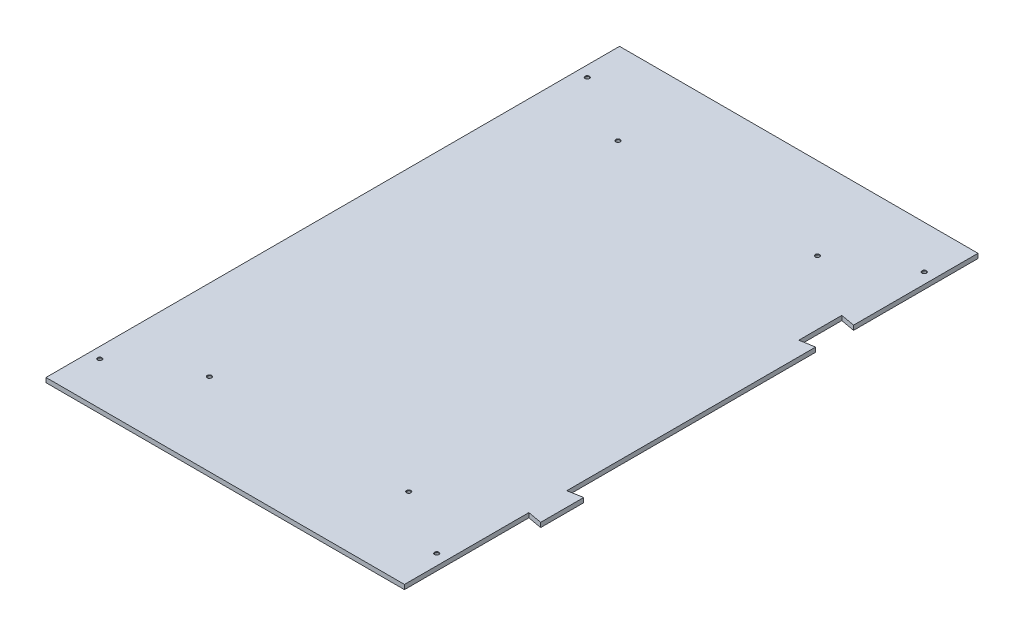
SolidWorks part; units mm, degrees
ref_plane "Front Plane" through (0, 0, 0) normal (0, 0, 1) x (1, 0, 0)
ref_plane "Top Plane" through (0, 0, 0) normal (0, 1, 0) x (1, 0, 0)
ref_plane "Right Plane" through (0, 0, 0) normal (1, 0, 0) x (0, 0, -1)
sketch "Sketch1" plane through (0, 0, 0) normal (0, 1, 0) x (1, 0, 0)
  line L0 (0, 0) -> (-99.9329, 0) construction
  line L1 (0, -19.2585) -> (0, 19.2585) construction
  line L2 (0, 86.7633) -> (-10, 85)
  line L3 (-10, 85) -> (-10, 115)
  line L4 (-10, 115) -> (0, 113.2367)
  line L5 (0, 113.2367) -> (0, 200)
  line L6 (0, 200) -> (-250, 200)
  line L7 (-250, 200) -> (-250, -200)
  line L8 (-10, 100) -> (-3.183, 100) construction
  line L9 (0, -86.7633) -> (0, 86.7633)
  line L10 (-10, -100) -> (-3.183, -100) construction
  line L11 (0, -200) -> (-250, -200)
  line L12 (0, -113.2367) -> (0, -200)
  line L16 (0, -86.7633) -> (0, -113.2367) construction
  line L17 (0, -86.7633) -> (10, -85)
  line L18 (10, -100) -> (3.183, -100) construction
  line L19 (10, -85) -> (10, -115)
  line L20 (10, -115) -> (0, -113.2367)
  point P19 (-250, 0)
  dimension "D1" = 20
  dimension "D2" = 80
  dimension "D3" = 80
  dimension "D4" = 30
  dimension "D5" = 100
  dimension "D6" = 200
  dimension "D7" = 80
  dimension "D8" = 80
  dimension "D9" = 30
  dimension "D10" = 250
extrude "Boss-Extrude1" add sketch "Sketch1" along normal blind 3.175
sketch "Sketch2" plane through (0, 3.175, 0) normal (0, 1, 0) x (1, 0, 0)
  line L0 (-250, -142.5) -> (-25.2029, -142.5) construction
  line L1 (-250, 200) -> (-250, -200) construction
  line L2 (-250, -200) -> (0, -200) construction
  line L3 (-250, 0) -> (-187.6563, 0) construction
  line L4 (-250, 142.5) -> (-25.2029, 142.5) construction
  line L5 (-242.5, -200) -> (-242.5, 200) construction
  line L6 (0, 200) -> (-250, 200) construction
  line L7 (-242.5, -170) -> (0, -170) construction
  line L8 (0, -200) -> (0, -113.2367) construction
  line L9 (-7.5, -200) -> (-7.5, -128.5966) construction
  line L10 (-7.5, 200) -> (-7.5, 128.5966) construction
  circle A0 centre (-193.5399, -142.5) radius 5.8836
  circle A1 centre (-193.5399, 142.5) radius 5.8836
  circle A2 centre (-242.5, -170) radius 4.6437
  circle A3 centre (-242.5, 170) radius 4.6437
  circle A4 centre (-7.5, -170) radius 3.7603
  circle A5 centre (-7.5, 170) radius 3.7603
  point P30 (0, 0)
  dimension "D1" = 57.5
  dimension "D2" = 7.5
  dimension "D3" = 30
  dimension "D4" = 7.5
hole_wizard "M3x0.5 Tapped Hole1" positions "Sketch3" profile "Sketch4" tap size "M3x0.5" standard "ANSI Metric" end condition through all
sketch "Sketch3" plane through (0, 3.175, 0) normal (0, 1, 0) x (1, 0, 0)
  line L0 (-250, 142.5) -> (-25.2029, 142.5) construction
  line L1 (-250, -142.5) -> (-25.2029, -142.5) construction
  point P0 (-193.5399, 142.5)
  point P3 (-193.5399, -142.5)
  point P7 (-54.5165, 142.5)
  point P11 (-54.5165, -142.5)
  point P16 (-242.5, -170)
  point P19 (-242.5, 170)
  point P23 (-7.5, -170)
  point P26 (-7.5, 170)
sketch "Sketch4" plane through (-193.5399, 3.175, -142.5) normal (1, 0, 0) x (0, 0, 1)
  line L0 (0, 0) -> (0, 3.175)
  line L1 (0, 3.175) -> (1.25, 3.175)
  line L2 (1.25, 3.175) -> (1.25, 0.275)
  line L3 (1.25, 0.275) -> (1.525, 0)
  line L5 (1.525, 0) -> (0, 0)
  line L6 (-1.25, 0.275) -> (-1.525, 0) construction
  line L11 (0, -6.35) -> (0, 107.95) construction
  dimension "Thread Major Dia." = 2.5
  dimension "Thru Tap Drill Depth" = 3.175
  dimension "Near C'Sink Dia." = 3.05
  dimension "Near C'Sink Angle" = 90
